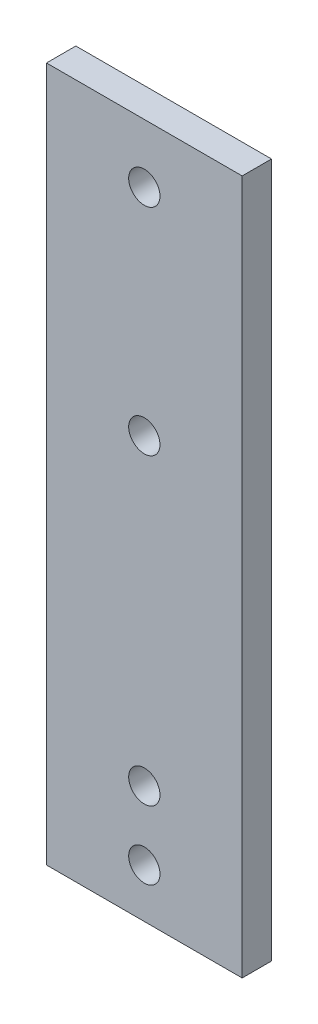
SolidWorks part; units mm, degrees
material "Thornel Mat VMA"
ref_plane "前视基准面" through (0, 0, 0) normal (0, 0, 1) x (1, 0, 0)
ref_plane "上视基准面" through (0, 0, 0) normal (0, 1, 0) x (1, 0, 0)
ref_plane "右视基准面" through (0, 0, 0) normal (1, 0, 0) x (0, 0, -1)
sketch "草图1" plane through (0, 0, 0) normal (0, 0, 1) x (1, 0, 0)
  line L0 (0, 0) -> (0, 35)
  line L1 (0, 35) -> (0, 71)
  line L2 (0, 71) -> (20, 71)
  line L3 (20, 71) -> (20, 35.4737)
  line L4 (20, 35.4737) -> (20, 0)
  line L5 (20, 0) -> (0, 0)
  line L6 (10, 71) -> (10, -10.1297) construction
  line L7 (10, 0) -> (10, 81.9038) construction
  circle A0 centre (10, 65) radius 1.6
  circle A1 centre (10, 43) radius 1.6
  circle A2 centre (10, 12) radius 1.6
  circle A3 centre (10, 5) radius 1.6
  dimension "D3" = 3.2
  dimension "D4" = 6
  dimension "D5" = 22
  dimension "D7" = 5
  dimension "D8" = 7
  dimension "D1" = 20
  dimension "D2" = 0
  dimension "D6" = 36
  dimension "D9" = 35
extrude "凸台-拉伸1" add sketch "草图1" along normal blind 3
